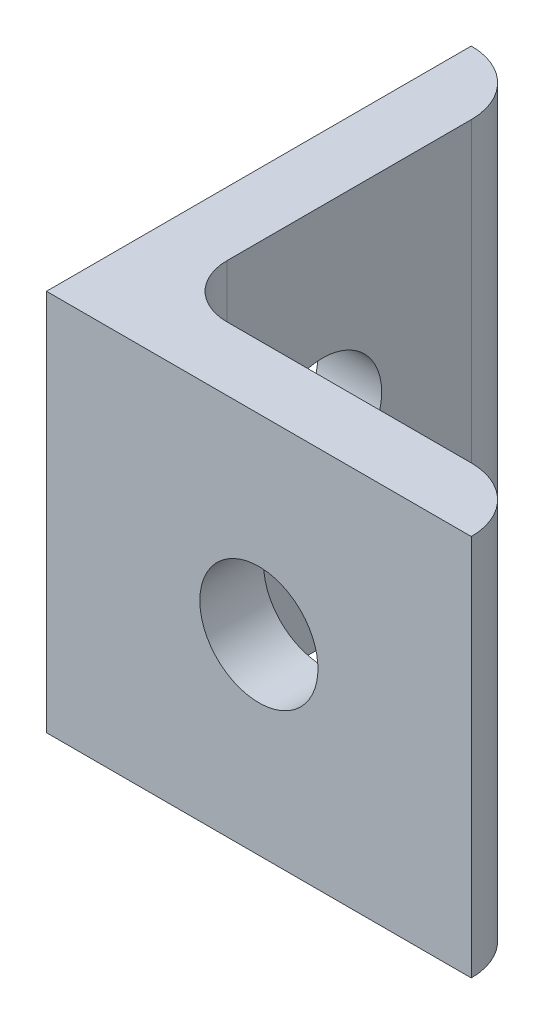
SolidWorks part; units mm, degrees
ref_plane "Front Plane" through (0, 0, 0) normal (0, 0, 1) x (1, 0, 0)
ref_plane "Top Plane" through (0, 0, 0) normal (0, 1, 0) x (1, 0, 0)
ref_plane "Right Plane" through (0, 0, 0) normal (1, 0, 0) x (0, 0, -1)
sketch "Sketch1" plane through (0, 0, 0) normal (0, 1, 0) x (1, 0, 0)
  line L0 (0, 0) -> (0, 20)
  line L1 (0, 0) -> (20, 0)
  line L3 (3, 17) -> (3, 5.5)
  line L4 (5.5, 3) -> (17, 3)
  line L6 (0, 20) -> (20, 20) construction
  line L7 (20, 0) -> (20, 20) construction
  arc A0 (0, 20) -> (3, 17) centre (0, 17) cw
  arc A1 (20, 0) -> (17, 3) centre (17, 0) ccw
  arc A2 (5.5, 3) -> (3, 5.5) centre (5.5, 5.5) cw
  point P5 (20.4753, 20)
  point P7 (20, 20)
  point P12 (19.6129, 20)
  dimension "D3" = 3
  dimension "D4" = 2.5
  dimension "D1" = 20
  dimension "D2" = 3
extrude "Boss-Extrude1" add sketch "Sketch1" along normal mid plane 18
sketch "Sketch2" plane through (0, 0, -3) normal (0, 0, -1) x (-1, 0, 0)
  line L0 (-17, 9) -> (-5.5, 9) construction
  line L2 (0, 9) -> (0, -9) construction
  circle A0 centre (-10, 0) radius 2.78
  point P6 (0, 0)
  dimension "D1" = 5.56
  dimension "D2" = 9
  dimension "D3" = 10
extrude "Cut-Extrude1" cut sketch "Sketch2" against normal through all
sketch "Sketch3" plane through (3, 0, 0) normal (1, 0, 0) x (0, 0, -1)
  line L1 (20, 9) -> (20, -9) construction
  line L2 (0, 9) -> (0, -9) construction
  circle A0 centre (10, 0) radius 2.78
  point P4 (0, 0)
  point P7 (20, 0)
  dimension "D1" = 10
  dimension "D2" = 5.56
extrude "Cut-Extrude2" cut sketch "Sketch3" against normal through all
